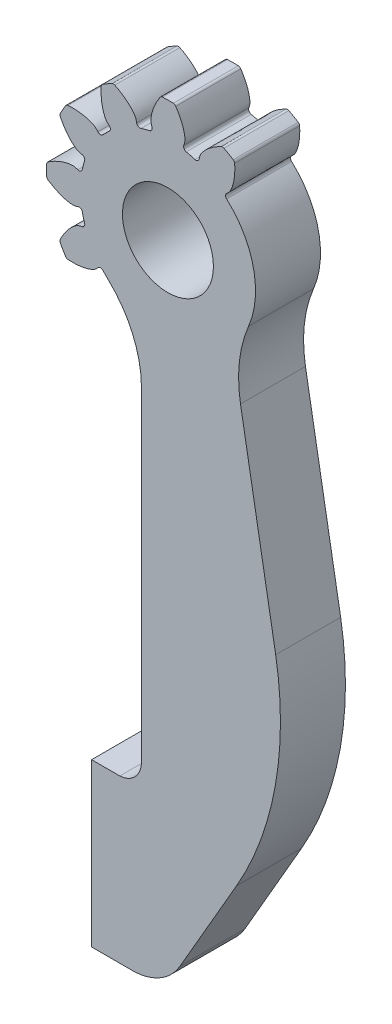
SolidWorks part; units mm, degrees
ref_plane "Plan de face" through (0, 0, 0) normal (0, 0, 1) x (1, 0, 0)
ref_plane "Plan de dessus" through (0, 0, 0) normal (0, 1, 0) x (1, 0, 0)
ref_plane "Plan de droite" through (0, 0, 0) normal (1, 0, 0) x (0, 0, -1)
sketch "Esquisse1" plane through (0, 0, 0) normal (0, 0, 1) x (1, 0, 0)
  line L0 (5.9075, 12.3265) -> (8.6161, -3.0347)
  line L1 (5.6008, -19.939) -> (1.2511, -27.4729)
  line L2 (-2.3204, -29.5917) -> (-5.551, -29.5917)
  line L3 (-5.551, -29.5917) -> (-5.551, -17.1075)
  line L4 (-5.551, -17.1075) -> (-3.3787, -17.1075)
  line L5 (-1.7175, -15.3502) -> (-1.7175, 9.7013)
  circle A0 centre (0.3231, 20.45) radius 3.5
  arc A1 (4.85, 25.8402) -> (4.8388, 25.4536) centre (5.009, 25.6421) ccw
  arc A2 (6.5305, 17.824) -> (4.8388, 25.4536) centre (0.3231, 20.45) ccw
  arc A4 (6.5305, 17.824) -> (5.9075, 12.3265) centre (15.5192, 14.0213) ccw
  arc A5 (5.6008, -19.939) -> (8.6161, -3.0347) centre (-16.2576, -7.319) ccw
  arc A6 (-2.3204, -29.5917) -> (1.2511, -27.4729) centre (-2.4208, -25.3529) ccw
  arc A7 (-3.3787, -17.1075) -> (-1.7175, -15.3502) centre (-3.4775, -15.3502) ccw
  arc A8 (-1.7175, 9.7013) -> (-4.2866, 15.5328) centre (-9.8469, 9.6016) ccw
  arc A9 (-4.6805, 15.9343) -> (-4.2866, 15.5328) centre (0.3231, 20.45) ccw
  arc A10 (-4.6805, 15.9343) -> (-5.0671, 15.9231) centre (-4.869, 15.7641) ccw
  arc A11 (-7.5506, 15.426) -> (-7.3642, 15.3156) centre (-7.3483, 15.5551) ccw
  arc A12 (-7.9647, 16.1432) -> (-7.5506, 15.426) centre (0.3231, 20.45) ccw
  arc A13 (-7.9671, 16.3598) -> (-7.9647, 16.1432) centre (-7.7517, 16.2539) ccw
  arc A14 (-6.2924, 18.0454) -> (-6.0894, 18.3746) centre (-6.3311, 18.2964) ccw
  arc A15 (-6.268, 19.0411) -> (-6.0894, 18.3746) centre (0.3231, 20.45) ccw
  arc A16 (-6.268, 19.0411) -> (-6.6084, 19.2247) centre (-6.5164, 18.988) ccw
  arc A17 (-9.0077, 20.0359) -> (-8.9015, 19.8471) centre (-8.768, 20.0466) ccw
  arc A18 (-9.0077, 20.8641) -> (-9.0077, 20.0359) centre (0.3231, 20.45) ccw
  arc A19 (-8.9015, 21.0529) -> (-9.0077, 20.8641) centre (-8.768, 20.8534) ccw
  arc A20 (-6.6084, 21.6753) -> (-6.268, 21.8589) centre (-6.5164, 21.912) ccw
  arc A21 (-6.0894, 22.5254) -> (-6.268, 21.8589) centre (0.3231, 20.45) ccw
  arc A22 (-6.0894, 22.5254) -> (-6.2924, 22.8546) centre (-6.3311, 22.6036) ccw
  arc A23 (-7.9647, 24.7568) -> (-7.9671, 24.5402) centre (-7.7517, 24.6461) ccw
  arc A24 (-7.5506, 25.474) -> (-7.9647, 24.7568) centre (0.3231, 20.45) ccw
  arc A25 (-7.3642, 25.5844) -> (-7.5506, 25.474) centre (-7.3483, 25.3449) ccw
  arc A26 (-5.0671, 24.9769) -> (-4.6805, 24.9657) centre (-4.869, 25.1359) ccw
  arc A27 (-4.1926, 25.4536) -> (-4.6805, 24.9657) centre (0.3231, 20.45) ccw
  arc A28 (-4.1926, 25.4536) -> (-4.2038, 25.8402) centre (-4.3628, 25.6421) ccw
  arc A29 (-4.7009, 28.3237) -> (-4.8113, 28.1373) centre (-4.5718, 28.1214) ccw
  arc A30 (-3.9837, 28.7378) -> (-4.7009, 28.3237) centre (0.3231, 20.45) ccw
  arc A31 (-3.7671, 28.7402) -> (-3.9837, 28.7378) centre (-3.873, 28.5248) ccw
  arc A32 (-2.0815, 27.0655) -> (-1.7523, 26.8625) centre (-1.8305, 27.1042) ccw
  arc A33 (-1.0858, 27.0411) -> (-1.7523, 26.8625) centre (0.3231, 20.45) ccw
  arc A34 (-1.0858, 27.0411) -> (-0.9022, 27.3815) centre (-1.1389, 27.2895) ccw
  arc A35 (-0.091, 29.7808) -> (-0.2798, 29.6746) centre (-0.0803, 29.5411) ccw
  arc A36 (0.7372, 29.7808) -> (-0.091, 29.7808) centre (0.3231, 20.45) ccw
  arc A37 (0.926, 29.6746) -> (0.7372, 29.7808) centre (0.7265, 29.5411) ccw
  arc A38 (1.5484, 27.3815) -> (1.732, 27.0411) centre (1.7851, 27.2895) ccw
  arc A39 (2.3985, 26.8625) -> (1.732, 27.0411) centre (0.3231, 20.45) ccw
  arc A40 (2.3985, 26.8625) -> (2.7277, 27.0655) centre (2.4767, 27.1042) ccw
  arc A41 (4.6299, 28.7378) -> (4.4133, 28.7402) centre (4.5192, 28.5248) ccw
  arc A42 (5.3471, 28.3237) -> (4.6299, 28.7378) centre (0.3231, 20.45) ccw
  arc A43 (5.4575, 28.1373) -> (5.3471, 28.3237) centre (5.218, 28.1214) ccw
  spline S0 degree 3 poles (5.4575, 28.1373) (5.4746, 27.8801) (5.475, 27.6162) (5.4418, 27.2507) (5.4309, 27.1591) (5.3865, 26.8773) (5.3455, 26.686) (5.2482, 26.4134) (5.2242, 26.3509) (5.1703, 26.2334) (5.1458, 26.1815) (5.0706, 26.059) (5.0149, 25.986) (4.9019, 25.8832) (4.8771, 25.862) (4.85, 25.8402) knots 0 0 0 0 0.40138 0.40138 0.532597 0.532597 0.795032 0.795032 0.872293 0.872293 0.929035 0.929035 0.985778 0.985778 1 1 1 1
  spline S1 degree 3 poles (-5.0671, 15.9231) (-5.1917, 15.7679) (-5.2999, 15.6912) (-5.4757, 15.5904) (-5.5556, 15.5584) (-5.7131, 15.4976) (-5.7884, 15.473) (-6.0298, 15.4029) (-6.1881, 15.3719) (-6.4977, 15.3267) (-6.6477, 15.3139) (-6.989, 15.2995) (-7.178, 15.3032) (-7.3642, 15.3156) knots 0 0 0 0 0.081188 0.081188 0.177126 0.177126 0.273064 0.273064 0.491379 0.491379 0.709693 0.709693 1 1 1 1
  spline S2 degree 3 poles (-7.9671, 16.3598) (-7.8533, 16.5911) (-7.7217, 16.8198) (-7.5101, 17.1198) (-7.4549, 17.1936) (-7.2756, 17.4155) (-7.1444, 17.5607) (-6.9238, 17.7481) (-6.8718, 17.7902) (-6.7665, 17.865) (-6.7192, 17.8978) (-6.5929, 17.9662) (-6.5081, 18.0016) (-6.3588, 18.0341) (-6.3268, 18.0401) (-6.2924, 18.0454) knots 0 0 0 0 0.40138 0.40138 0.532597 0.532597 0.795032 0.795032 0.872293 0.872293 0.929035 0.929035 0.985778 0.985778 1 1 1 1
  spline S3 degree 3 poles (-6.6084, 19.2247) (-6.794, 19.1526) (-6.926, 19.1403) (-7.1286, 19.1409) (-7.2138, 19.1531) (-7.3806, 19.1792) (-7.4581, 19.1955) (-7.7023, 19.2555) (-7.8548, 19.3079) (-8.1455, 19.4235) (-8.2818, 19.4874) (-8.5846, 19.6455) (-8.7465, 19.7433) (-8.9015, 19.8471) knots 0 0 0 0 0.081188 0.081188 0.177126 0.177126 0.273064 0.273064 0.491379 0.491379 0.709693 0.709693 1 1 1 1
  spline S4 degree 3 poles (-8.9015, 21.0529) (-8.6873, 21.1963) (-8.459, 21.3285) (-8.1258, 21.4826) (-8.041, 21.5189) (-7.7748, 21.6214) (-7.5886, 21.6815) (-7.3039, 21.7335) (-7.2378, 21.744) (-7.1091, 21.7561) (-7.0518, 21.7609) (-6.9082, 21.7569) (-6.8171, 21.7452) (-6.6716, 21.6988) (-6.6408, 21.6879) (-6.6084, 21.6753) knots 0 0 0 0 0.40138 0.40138 0.532597 0.532597 0.795032 0.795032 0.872293 0.872293 0.929035 0.929035 0.985778 0.985778 1 1 1 1
  spline S5 degree 3 poles (-6.2924, 22.8546) (-6.4892, 22.8849) (-6.6097, 22.9403) (-6.7848, 23.0421) (-6.8525, 23.0953) (-6.9839, 23.2013) (-7.0428, 23.2542) (-7.2243, 23.4283) (-7.3302, 23.5498) (-7.5242, 23.7953) (-7.6103, 23.9188) (-7.7934, 24.2072) (-7.8847, 24.3728) (-7.9671, 24.5402) knots 0 0 0 0 0.081188 0.081188 0.177126 0.177126 0.273064 0.273064 0.491379 0.491379 0.709693 0.709693 1 1 1 1
  spline S6 degree 3 poles (-7.3642, 25.5844) (-7.107, 25.6015) (-6.8431, 25.6019) (-6.4776, 25.5687) (-6.386, 25.5578) (-6.1042, 25.5134) (-5.9129, 25.4724) (-5.6403, 25.3751) (-5.5778, 25.3511) (-5.4603, 25.2972) (-5.4084, 25.2727) (-5.2859, 25.1975) (-5.2129, 25.1418) (-5.1101, 25.0288) (-5.0889, 25.004) (-5.0671, 24.9769) knots 0 0 0 0 0.40138 0.40138 0.532597 0.532597 0.795032 0.795032 0.872293 0.872293 0.929035 0.929035 0.985778 0.985778 1 1 1 1
  spline S7 degree 3 poles (-4.2038, 25.8402) (-4.359, 25.9648) (-4.4357, 26.073) (-4.5365, 26.2488) (-4.5685, 26.3287) (-4.6293, 26.4862) (-4.6539, 26.5615) (-4.724, 26.8029) (-4.755, 26.9612) (-4.8002, 27.2708) (-4.813, 27.4208) (-4.8274, 27.7621) (-4.8237, 27.9511) (-4.8113, 28.1373) knots 0 0 0 0 0.081188 0.081188 0.177126 0.177126 0.273064 0.273064 0.491379 0.491379 0.709693 0.709693 1 1 1 1
  spline S8 degree 3 poles (-3.7671, 28.7402) (-3.5358, 28.6264) (-3.3071, 28.4948) (-3.0071, 28.2833) (-2.9333, 28.228) (-2.7114, 28.0487) (-2.5662, 27.9175) (-2.3788, 27.6969) (-2.3367, 27.6449) (-2.2619, 27.5396) (-2.2291, 27.4923) (-2.1607, 27.366) (-2.1253, 27.2812) (-2.0928, 27.1319) (-2.0868, 27.0999) (-2.0815, 27.0655) knots 0 0 0 0 0.40138 0.40138 0.532597 0.532597 0.795032 0.795032 0.872293 0.872293 0.929035 0.929035 0.985778 0.985778 1 1 1 1
  spline S9 degree 3 poles (-0.9022, 27.3815) (-0.9743, 27.5671) (-0.9866, 27.6991) (-0.986, 27.9017) (-0.9738, 27.9869) (-0.9477, 28.1537) (-0.9313, 28.2312) (-0.8714, 28.4754) (-0.819, 28.6279) (-0.7034, 28.9186) (-0.6395, 29.0549) (-0.4814, 29.3577) (-0.3836, 29.5196) (-0.2798, 29.6746) knots 0 0 0 0 0.081188 0.081188 0.177126 0.177126 0.273064 0.273064 0.491379 0.491379 0.709693 0.709693 1 1 1 1
  spline S10 degree 3 poles (0.926, 29.6746) (1.0694, 29.4604) (1.2017, 29.2321) (1.3557, 28.8989) (1.392, 28.8141) (1.4945, 28.5479) (1.5546, 28.3617) (1.6066, 28.077) (1.6171, 28.0109) (1.6292, 27.8822) (1.634, 27.8249) (1.63, 27.6813) (1.6183, 27.5902) (1.5719, 27.4447) (1.561, 27.4139) (1.5484, 27.3815) knots 0 0 0 0 0.40138 0.40138 0.532597 0.532597 0.795032 0.795032 0.872293 0.872293 0.929035 0.929035 0.985778 0.985778 1 1 1 1
  spline S11 degree 3 poles (2.7277, 27.0655) (2.758, 27.2623) (2.8134, 27.3828) (2.9152, 27.5579) (2.9684, 27.6256) (3.0744, 27.757) (3.1273, 27.8159) (3.3014, 27.9974) (3.4229, 28.1033) (3.6684, 28.2973) (3.7919, 28.3834) (4.0803, 28.5665) (4.2459, 28.6578) (4.4133, 28.7402) knots 0 0 0 0 0.081188 0.081188 0.177126 0.177126 0.273064 0.273064 0.491379 0.491379 0.709693 0.709693 1 1 1 1
  dimension "D1" = 7
  dimension "D2" = 6.74
  dimension "D3" = 8.13
  dimension "D4" = 9.76
  dimension "D5" = 25.24
extrude "Boss.-Extru.1" add sketch "Esquisse1" along normal blind 5
